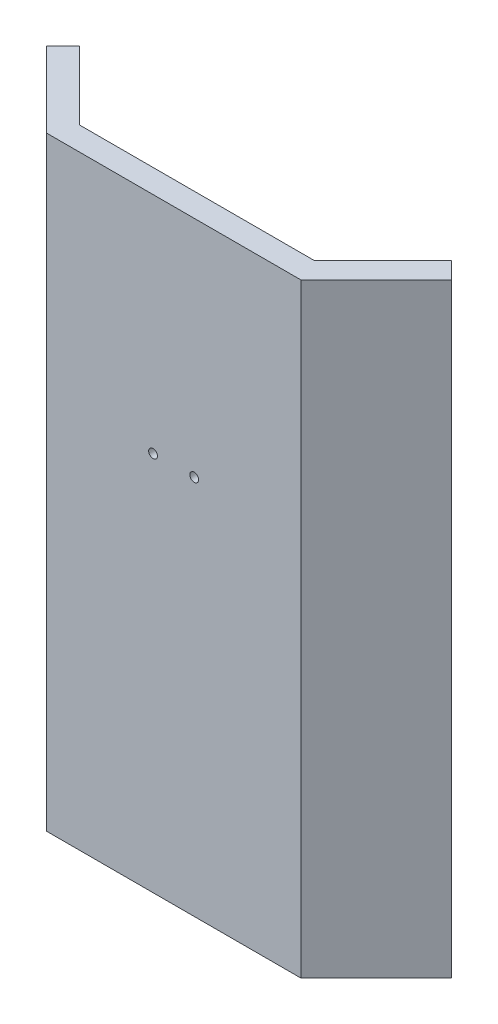
SolidWorks part; units mm, degrees
material "3.0205 (EN-AW 1200)"
ref_plane "Alzado" through (0, 0, 0) normal (0, 0, 1) x (1, 0, 0)
ref_plane "Planta" through (0, 0, 0) normal (0, 1, 0) x (1, 0, 0)
ref_plane "Vista lateral" through (0, 0, 0) normal (1, 0, 0) x (0, 0, -1)
sketch "Croquis1" plane through (0, 0, 0) normal (0, 1, 0) x (1, 0, 0)
  line L0 (-40, 0) -> (40, 0)
  line L1 (40, 0) -> (63.3345, 23.3345)
  line L2 (-40, 0) -> (-63.3345, 23.3345)
  line L3 (-43.3137, -8) -> (-68.9914, 17.6777)
  line L5 (-43.3137, -8) -> (43.3137, -8)
  line L6 (43.3137, -8) -> (68.9914, 17.6777)
  line L7 (-68.9914, 17.6777) -> (-63.3345, 23.3345)
  line L8 (63.3345, 23.3345) -> (68.9914, 17.6777)
  dimension "D1" = 33
  dimension "D2" = 33
  dimension "D3" = 8
  dimension "D4" = 80
  dimension "D5" = 135
  dimension "D6" = 135
extrude "Saliente-Extruir1" add sketch "Croquis1" along normal blind 206 contours L5 L6 L8 L1 L0 L2 L7 L3
sketch "Croquis2" plane through (0, 0, 0) normal (0, 0, -1) x (-1, 0, 0)
  line L0 (0, 0) -> (0, 206) construction
  line L1 (40, 206) -> (-40, 206) construction
  line L2 (34, 6.4041) -> (34, 12.4041)
  line L3 (-34, 6.4041) -> (-24, 6.4041)
  line L4 (-34, 6.4041) -> (-34, 12.4041)
  line L5 (-34, 12.4041) -> (-24, 12.4041)
  line L6 (-24, 6.4041) -> (-24, 12.4041)
  line L7 (34, 6.4041) -> (24, 6.4041)
  line L8 (24, 6.4041) -> (24, 12.4041)
  line L9 (34, 12.4041) -> (24, 12.4041)
  line L10 (-40, 206) -> (-40, 0) construction
  dimension "D1" = 10
  dimension "D2" = 6
  dimension "D3" = 6
extrude "Saliente-Extruir2" add sketch "Croquis2" along normal blind 10
sketch "Croquis3" plane through (0, 6.4041, 0) normal (0, -1, 0) x (1, 0, 0)
  line L0 (29, -10) -> (29, 0)
  line L1 (34, -10) -> (24, -10) construction
  line L2 (34, 0) -> (24, 0) construction
  line L3 (-34, 0) -> (-24, -10)
  circle A0 centre (29, -5) radius 1.5
  circle A1 centre (-29, -5) radius 1.5
  dimension "D1" = 3
  dimension "D2" = 3
extrude "Cortar-Extruir1" cut sketch "Croquis3" against normal blind 10 contours L3 A1 | L3 A1 | L0 A0 | L0 A0
sketch "Croquis4" plane through (0, 0, 8) normal (0, 0, 1) x (1, 0, 0)
  line L0 (-43.3137, 206) -> (43.3137, 206) construction
  line L2 (-7.0001, 129.596) -> (-6.8632, 131.0897)
  line L3 (6.8631, 131.0897) -> (6.9999, 129.596)
  line L4 (-7.0001, 129.596) -> (-7.0001, 168.9786)
  circle A0 centre (-7.0001, 129.596) radius 1.5
  circle A1 centre (6.9999, 129.596) radius 1.5
  dimension "D2" = 3
  dimension "D3" = 3
  dimension "D1" = 76.404
  dimension "D4" = 14
extrude "Cortar-Extruir4" cut sketch "Croquis4" against normal blind 10 contours A1 | A0
